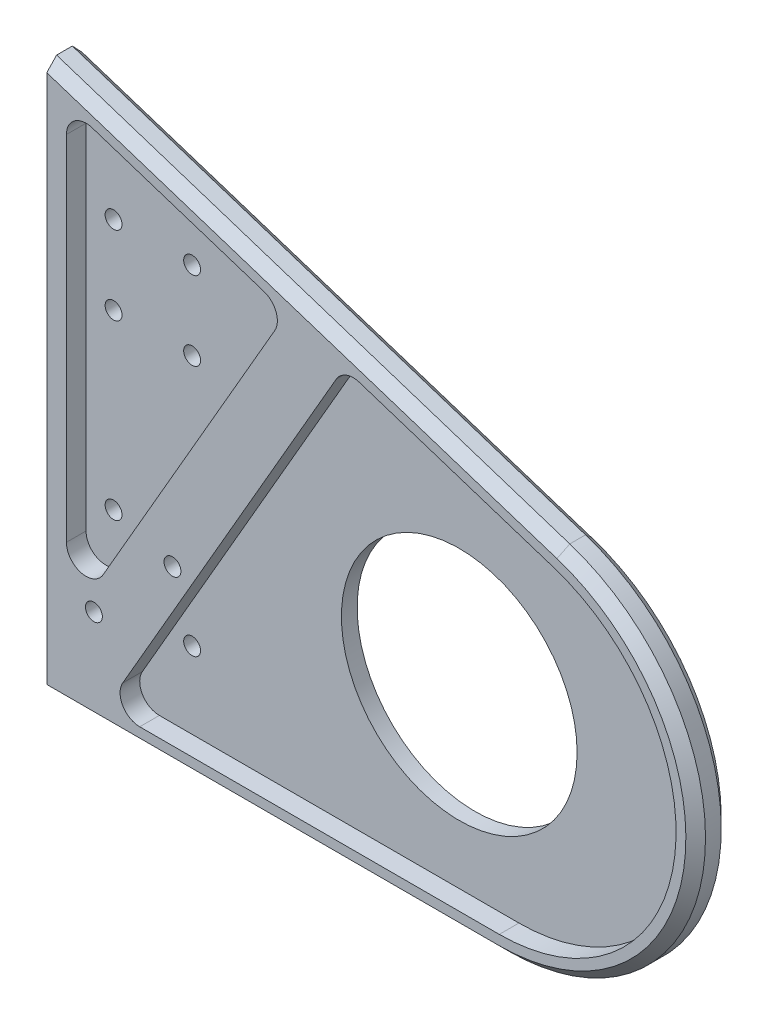
SolidWorks part; units mm, degrees
material "6061 合金"
ref_plane "前视基准面" through (0, 0, 0) normal (0, 0, 1) x (1, 0, 0)
ref_plane "上视基准面" through (0, 0, 0) normal (0, 1, 0) x (1, 0, 0)
ref_plane "右视基准面" through (0, 0, 0) normal (1, 0, 0) x (0, 0, -1)
other "Configuration Table"
sketch "草图1" plane through (0, 0, 0) normal (0, 0, 1) x (1, 0, 0)
  line L0 (0, 0) -> (0, 280)
  line L1 (0, 280) -> (861.7514, 0)
  line L3 (861.7514, 0) -> (0, 0)
  circle A0 centre (200, 100) radius 85 construction
  circle A1 centre (200, 100) radius 60
  dimension "D1" = 170
  dimension "D4" = 120
  dimension "D2" = 200
  dimension "D3" = 72
  dimension "D5" = 280
  dimension "D6" = 100
extrude "凸台-拉伸1" add sketch "草图1" along normal blind 8
fillet "圆角1" radius 100 1 edges at (861.7514, 0, 4)
sketch "草图2" plane through (0, 0, 8) normal (0, 0, 1) x (1, 0, 0)
  line L0 (10, 266.2362) -> (10, 35.359)
  line L1 (30, 10) -> (230.3762, 10)
  line L2 (10, 266.2362) -> (122.2414, 229.7667)
  line L3 (0, 0) -> (230.3762, 0)
  line L4 (261.2779, 195.1057) -> (0, 280)
  line L5 (0, 280) -> (0, 0)
  line L6 (0, 0) -> (230.3762, 0)
  line L7 (261.2779, 195.1057) -> (0, 280)
  line L8 (0, 280) -> (0, 0)
  line L9 (10, 35.359) -> (122.2414, 229.7667)
  line L10 (30, 10) -> (151.4105, 220.2891)
  line L11 (151.4105, 220.2891) -> (258.1878, 185.5951)
  line L12 (10, 35.359) -> (10, 10) construction
  line L13 (10, 10) -> (30, 10) construction
  arc A0 (230.3762, 10) -> (258.1878, 185.5951) centre (230.3762, 100) ccw
  arc A1 (230.3762, 0) -> (261.2779, 195.1057) centre (230.3762, 100) ccw
  arc A2 (230.3762, 0) -> (261.2779, 195.1057) centre (230.3762, 100) ccw
  dimension "D5" = 10
  dimension "D2" = 10
  dimension "D3" = 10
  dimension "D4" = 10
  dimension "D6" = 30
  dimension "D7" = 60
  dimension "D8" = 20
  dimension "D1" = 0
extrude "凸台-拉伸2" add sketch "草图2" along normal blind 10
fillet "圆角2" radius 10 5 edges at (10, 35.359, 13) (30, 10, 13) (122.2414, 229.7667, 13) (151.4105, 220.2891, 13) (10, 266.2362, 13)
chamfer "倒角1" distance 5 angle 45 6 edges at (130.639, 237.5528, 0) (115.1881, 0, 0) (329.1451, 84.3566, 0) (115.1881, 0, 18) (130.639, 237.5528, 18) (329.1451, 84.3566, 18)
sketch "草图3" plane through (0, 0, 0) normal (0, 0, -1) x (-1, 0, 0)
  line L0 (0, 274.7427) -> (0, 5) construction
  line L1 (-78, 236) -> (0, 236) construction
  line L2 (-78, 236) -> (-78, 158) construction
  line L3 (-78, 158) -> (0, 158) construction
  line L4 (0, 236) -> (0, 158) construction
  line L5 (-78, 108) -> (0, 108) construction
  line L6 (-78, 108) -> (-78, 30) construction
  line L7 (-78, 30) -> (0, 30) construction
  line L8 (0, 108) -> (0, 30) construction
  line L9 (0, 0) -> (-230.3762, 0) construction
  circle A0 centre (-64, 217) radius 4.3
  circle A1 centre (-64, 177) radius 4.3
  circle A2 centre (-24, 217) radius 4.3
  circle A3 centre (-24, 177) radius 4.3
  circle A4 centre (-64, 89) radius 4.3
  circle A5 centre (-24, 89) radius 4.3
  circle A6 centre (-64, 49) radius 4.3
  circle A7 centre (-24, 49) radius 4.3
  point P30 (-79.4903, 31.9733)
  dimension "D7" = 8.6
  dimension "D16" = 8.6
  dimension "D1" = 78
  dimension "D2" = 78
  dimension "D3" = 78
  dimension "D4" = 78
  dimension "D5" = 30
  dimension "D6" = 50
  dimension "D8" = 19
  dimension "D9" = 19
  dimension "D10" = 19
  dimension "D11" = 19
  dimension "D12" = 14
  dimension "D13" = 14
  dimension "D14" = 24
  dimension "D15" = 24
  dimension "D17" = 19
  dimension "D18" = 19
  dimension "D19" = 19
  dimension "D20" = 19
  dimension "D21" = 14
  dimension "D22" = 14
  dimension "D23" = 24
  dimension "D24" = 24
extrude "切除-拉伸1" cut sketch "草图3" against normal through all both
